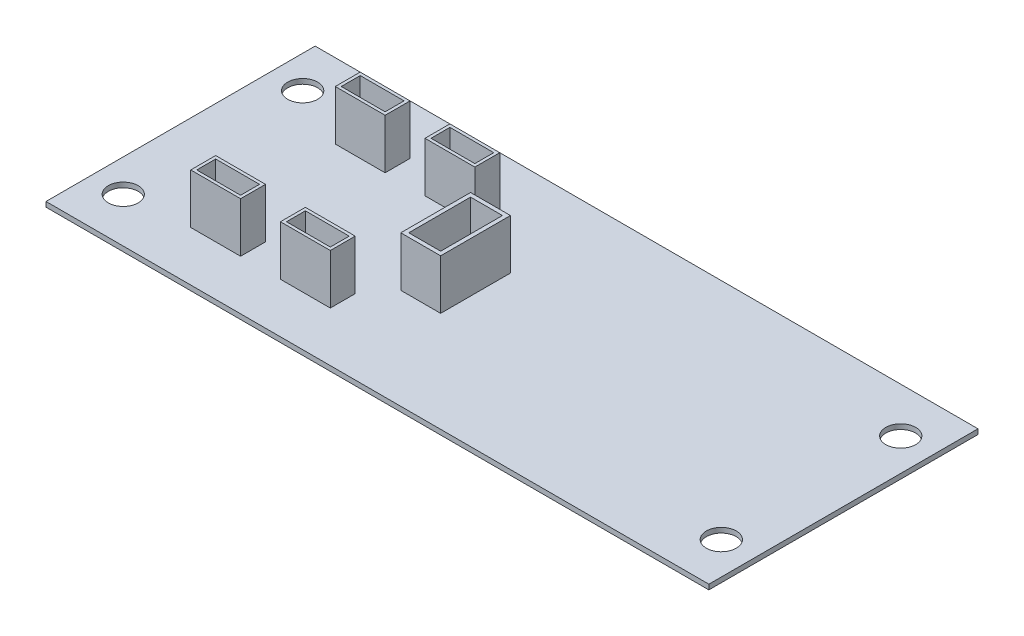
SolidWorks part; units mm, degrees
ref_plane "Front Plane" through (0, 0, 0) normal (0, 0, 1) x (1, 0, 0)
ref_plane "Top Plane" through (0, 0, 0) normal (0, 1, 0) x (1, 0, 0)
ref_plane "Right Plane" through (0, 0, 0) normal (1, 0, 0) x (0, 0, -1)
sketch "Sketch1" plane through (0, 0, 0) normal (0, 1, 0) x (1, 0, 0)
  line L1 (-33.25, 13.5) -> (33.25, 13.5)
  line L2 (-33.25, 13.5) -> (-33.25, -13.5)
  line L3 (-33.25, -13.5) -> (33.25, -13.5)
  line L4 (33.25, 13.5) -> (33.25, -13.5)
  line L5 (-33.25, 13.5) -> (33.25, -13.5) construction
  line L6 (-33.25, -13.5) -> (33.25, 13.5) construction
  circle A0 centre (-30, 9) radius 1.5
  circle A1 centre (-30, -9) radius 1.5
  circle A2 centre (30, 9) radius 1.5
  circle A3 centre (30, -9) radius 1.5
  point P0 (0, 0)
  dimension "D7" = 3
  dimension "D8" = 3
  dimension "D9" = 3
  dimension "D10" = 3
  dimension "D1" = 27
  dimension "D2" = 66.5
  dimension "D3" = 18
  dimension "D4" = 3.25
  dimension "D5" = 60
  dimension "D6" = 4.5
extrude "Boss-Extrude1" add sketch "Sketch1" along normal blind 0.5
sketch "Sketch2" plane through (0, 0.5, 0) normal (0, 1, 0) x (1, 0, 0)
  line L0 (33.25, 13.5) -> (-33.25, 13.5) construction
  line L1 (-23.7289, 6) -> (-9.7289, 6) construction
  line L2 (-23.7289, 6) -> (-23.7289, -6) construction
  line L3 (-23.7289, -6) -> (-9.7289, -6) construction
  line L4 (-9.7289, 6) -> (-9.7289, -6) construction
  line L6 (-23.7289, 6) -> (-23.7289, 8.5)
  line L7 (-23.7289, 8.5) -> (-18.7289, 8.5)
  line L8 (-18.7289, 8.5) -> (-18.7289, 6)
  line L9 (-18.7289, 6) -> (-23.7289, 6)
  line L10 (-23.4289, 8.2) -> (-19.0289, 8.2)
  line L11 (-19.0289, 8.2) -> (-19.0289, 6.3)
  line L12 (-19.0289, 6.3) -> (-23.4289, 6.3)
  line L13 (-23.4289, 6.3) -> (-23.4289, 8.2)
  line L14 (-16.7289, 6) -> (-16.7289, -6) construction
  line L15 (-14.4289, 6.3) -> (-10.0289, 6.3)
  line L16 (-10.0289, 8.2) -> (-14.4289, 8.2)
  line L17 (-9.7289, 8.5) -> (-14.7289, 8.5)
  line L18 (-14.7289, 6) -> (-9.7289, 6)
  line L19 (-9.7289, 6) -> (-9.7289, 8.5)
  line L20 (-10.0289, 6.3) -> (-10.0289, 8.2)
  line L21 (-14.4289, 8.2) -> (-14.4289, 6.3)
  line L22 (-14.7289, 8.5) -> (-14.7289, 6)
  line L23 (-23.7289, 0) -> (-9.7289, 0) construction
  line L24 (-23.7289, -6) -> (-9.7289, -6) construction
  line L25 (-14.7289, -8.5) -> (-14.7289, -6)
  line L26 (-14.4289, -8.2) -> (-14.4289, -6.3)
  line L27 (-10.0289, -6.3) -> (-10.0289, -8.2)
  line L28 (-9.7289, -6) -> (-9.7289, -8.5)
  line L29 (-14.7289, -6) -> (-9.7289, -6)
  line L30 (-9.7289, -8.5) -> (-14.7289, -8.5)
  line L31 (-10.0289, -8.2) -> (-14.4289, -8.2)
  line L32 (-14.4289, -6.3) -> (-10.0289, -6.3)
  line L33 (-23.4289, -6.3) -> (-23.4289, -8.2)
  line L34 (-19.0289, -6.3) -> (-23.4289, -6.3)
  line L35 (-19.0289, -8.2) -> (-19.0289, -6.3)
  line L36 (-23.4289, -8.2) -> (-19.0289, -8.2)
  line L37 (-18.7289, -6) -> (-23.7289, -6)
  line L38 (-18.7289, -8.5) -> (-18.7289, -6)
  line L39 (-23.7289, -8.5) -> (-18.7289, -8.5)
  line L40 (-23.7289, -6) -> (-23.7289, -8.5)
  point P0 (-9.7289, 0)
  dimension "D1" = 14
  dimension "D2" = 12
  dimension "D3" = 13.5
  dimension "D4" = 2.5
  dimension "D5" = 5
  dimension "D6" = 0.3
extrude "Boss-Extrude2" add sketch "Sketch2" along normal blind 5
sketch "Sketch4" plane through (0, 0.5, 0) normal (0, 1, 0) x (1, 0, 0)
  line L0 (-4.1324, 3.1744) -> (-4.1324, -3.0256)
  line L1 (-7.7324, 3.5744) -> (-3.7324, 3.5744)
  line L2 (-7.7324, 3.5744) -> (-7.7324, -3.4256)
  line L3 (-7.7324, -3.4256) -> (-3.7324, -3.4256)
  line L4 (-3.7324, 3.5744) -> (-3.7324, -3.4256)
  line L5 (-7.7324, 3.5744) -> (-3.7324, -3.4256) construction
  line L6 (-7.7324, -3.4256) -> (-3.7324, 3.5744) construction
  line L7 (-7.3324, -3.0256) -> (-4.1324, -3.0256)
  line L8 (-7.3324, 3.1744) -> (-7.3324, -3.0256)
  line L9 (-7.3324, 3.1744) -> (-4.1324, 3.1744)
  point P0 (-5.7324, 0.0744)
  dimension "D1" = 7
  dimension "D2" = 4
  dimension "D3" = 0.4
extrude "Boss-Extrude3" add sketch "Sketch4" along normal blind 5
